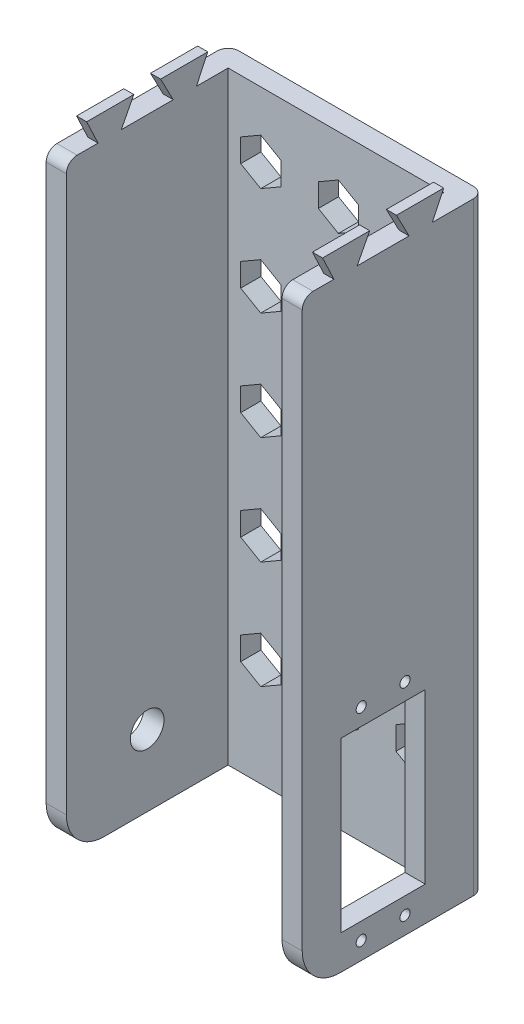
SolidWorks part; units mm, degrees
ref_plane "Front Plane" through (0, 0, 0) normal (0, 0, 1) x (1, 0, 0)
ref_plane "Top Plane" through (0, 0, 0) normal (0, 1, 0) x (1, 0, 0)
ref_plane "Right Plane" through (0, 0, 0) normal (1, 0, 0) x (0, 0, -1)
sketch "Sketch1" plane through (0, 0, 0) normal (0, 1, 0) x (1, 0, 0)
  line L0 (-38.9416, 17.4938) -> (21.3834, 17.4938)
  line L1 (21.3834, 17.4938) -> (21.3834, -25.3687)
  line L2 (21.3834, -25.3687) -> (16.6209, -25.3687)
  line L3 (16.6209, -25.3687) -> (16.6209, 12.7313)
  line L4 (16.6209, 12.7313) -> (-34.1791, 12.7313)
  line L5 (-34.1791, 12.7313) -> (-34.1791, -25.3687)
  line L6 (-34.1791, -25.3687) -> (-38.9416, -25.3687)
  line L7 (-38.9416, -25.3687) -> (-38.9416, 17.4938)
extrude "Boss-Extrude1" add sketch "Sketch1" along normal blind 152.4
sketch "Sketch2" plane through (21.3834, 0, 0) normal (1, 0, 0) x (0, 0, -1)
  line L0 (-25.3687, 38.1) -> (-6.3187, 38.1) construction
  line L1 (-25.3687, 152.4) -> (-25.3687, 0) construction
  line L2 (-6.3187, 38.1) -> (-6.3187, 0) construction
  line L3 (-25.3687, 0) -> (17.4938, 0) construction
  line L4 (-6.3187, 18.2562) -> (-11.4781, 18.2562) construction
  line L5 (-16.2406, 18.2562) -> (3.6031, 18.2562)
  line L6 (-16.2406, 18.2562) -> (-16.2406, 57.9437)
  line L7 (-16.2406, 57.9437) -> (3.6031, 57.9437)
  line L8 (3.6031, 18.2562) -> (3.6031, 57.9437)
  line L9 (-16.2406, 18.2562) -> (3.6031, 57.9437) construction
  line L10 (-16.2406, 57.9437) -> (3.6031, 18.2562) construction
  line L11 (-11.4781, 18.2562) -> (-11.4781, 14.2875) construction
  circle A0 centre (-11.4781, 14.2875) radius 1.1906
  circle A1 centre (-1.1594, 14.2875) radius 1.1906
  circle A2 centre (-1.1594, 61.9125) radius 1.1906
  circle A3 centre (-11.4781, 61.9125) radius 1.1906
  dimension "D1" = 19.05
  dimension "D2" = 38.1
  dimension "D3" = 19.8438
  dimension "D4" = 39.6875
extrude "Cut-Extrude1" cut sketch "Sketch2" against normal blind 6.35
sketch "Sketch3" plane through (21.3834, 0, 0) normal (1, 0, 0) x (0, 0, -1)
  line L0 (-20.5873, 5.6903) -> (-9.4704, 5.6903)
  line L1 (-9.4704, 5.6903) -> (-12.4312, 0)
  line L2 (-25.3687, 0) -> (17.4938, 0) construction
  line L3 (-12.4312, 0) -> (-17.9058, 0)
  line L4 (-17.9058, 0) -> (-20.5873, 5.6903)
  line L5 (-25.3687, 5.6903) -> (-15.0288, 5.6903) construction
  line L6 (-25.3687, 152.4) -> (-25.3687, 0) construction
  line L7 (-15.0288, 5.6903) -> (-15.1685, 0) construction
  line L8 (-15.1685, 0) -> (-25.3687, 0) construction
  line L9 (-25.3687, 0) -> (-6.3187, 0) construction
  line L10 (-6.3187, 0) -> (-6.3187, 14.3302) construction
  line L11 (-0.2063, 0) -> (5.2683, 0)
  line L12 (5.2683, 0) -> (7.9498, 5.6903)
  line L13 (-3.1671, 5.6903) -> (-0.2063, 0)
  line L14 (7.9498, 5.6903) -> (-3.1671, 5.6903)
  line L19 (-25.3687, 0) -> (12.7313, 0)
  line L20 (12.7313, 0) -> (12.7313, 152.4)
  line L21 (12.7313, 152.4) -> (-25.3687, 152.4)
  line L22 (-25.3687, 152.4) -> (-25.3687, 0)
  line L23 (-25.3687, 0) -> (12.7313, 0) construction
  dimension "D1" = 0
extrude "Cut-Extrude2" cut sketch "Sketch3" against normal blind 2.3813
sketch "Sketch4" plane through (-34.1791, 0, 0) normal (1, 0, 0) x (0, 0, -1)
  line L4 (-9.4704, 5.6903) -> (-20.5873, 5.6903)
  line L5 (-12.4312, 0) -> (-9.4704, 5.6903)
  line L6 (-17.9058, 0) -> (-12.4312, 0)
  line L7 (-20.5873, 5.6903) -> (-17.9058, 0)
  line L8 (-9.4704, 5.6903) -> (-20.5873, 5.6903)
  line L9 (-12.4312, 0) -> (-9.4704, 5.6903)
  line L10 (-17.9058, 0) -> (-12.4312, 0)
  line L11 (-20.5873, 5.6903) -> (-17.9058, 0)
  line L12 (5.2683, 0) -> (7.9498, 5.6903)
  line L13 (7.9498, 5.6903) -> (-3.1671, 5.6903)
  line L14 (-3.1671, 5.6903) -> (-0.2063, 0)
  line L15 (-0.2063, 0) -> (5.2683, 0)
  line L16 (5.2683, 0) -> (7.9498, 5.6903)
  line L17 (7.9498, 5.6903) -> (-3.1671, 5.6903)
  line L18 (-3.1671, 5.6903) -> (-0.2063, 0)
  line L19 (-0.2063, 0) -> (5.2683, 0)
  dimension "D1" = 0
  dimension "D2" = 0
extrude "Cut-Extrude3" cut sketch "Sketch4" against normal blind 2.3813
sketch "Sketch5" plane through (21.3834, 0, 0) normal (1, 0, 0) x (0, 0, -1)
  line L0 (-25.3687, 76.2) -> (28.2965, 76.2) construction
  line L1 (-25.3687, 152.4) -> (-25.3687, 0) construction
  line L2 (-3.1671, 146.7097) -> (-0.2063, 152.4) construction
  line L3 (-0.2063, 152.4) -> (5.2683, 152.4)
  line L4 (-9.4704, 5.6903) -> (-20.5873, 5.6903)
  line L5 (-12.4312, 0) -> (-9.4704, 5.6903)
  line L6 (-17.9058, 0) -> (-12.4312, 0)
  line L7 (-20.5873, 5.6903) -> (-17.9058, 0)
  line L8 (-9.4704, 5.6903) -> (-20.5873, 5.6903) construction
  line L9 (-12.4312, 0) -> (-9.4704, 5.6903) construction
  line L10 (-17.9058, 0) -> (-12.4312, 0) construction
  line L11 (-20.5873, 5.6903) -> (-17.9058, 0) construction
  line L12 (5.2683, 0) -> (7.9498, 5.6903)
  line L13 (7.9498, 5.6903) -> (-3.1671, 5.6903)
  line L14 (-3.1671, 5.6903) -> (-0.2063, 0)
  line L15 (-0.2063, 0) -> (5.2683, 0)
  line L16 (5.2683, 0) -> (7.9498, 5.6903) construction
  line L17 (7.9498, 5.6903) -> (-3.1671, 5.6903) construction
  line L18 (-3.1671, 5.6903) -> (-0.2063, 0) construction
  line L19 (-0.2063, 0) -> (5.2683, 0) construction
  line L20 (5.2683, 152.4) -> (7.9498, 146.7097) construction
  line L21 (7.9498, 146.7097) -> (-3.1671, 146.7097) construction
  line L22 (-20.5873, 146.7097) -> (-17.9058, 152.4) construction
  line L23 (-17.9058, 152.4) -> (-12.4312, 152.4)
  line L24 (-12.4312, 152.4) -> (-9.4704, 146.7097) construction
  line L25 (-9.4704, 146.7097) -> (-20.5873, 146.7097) construction
  line L26 (-25.3687, 152.4) -> (17.4938, 152.4) construction
  line L27 (7.9498, 158.0903) -> (-3.1671, 158.0903)
  line L28 (5.2683, 152.4) -> (7.9498, 158.0903)
  line L29 (-3.1671, 158.0903) -> (-0.2063, 152.4)
  line L30 (-12.4312, 152.4) -> (-9.4704, 158.0903)
  line L31 (-9.4704, 158.0903) -> (-20.5873, 158.0903)
  line L32 (-20.5873, 158.0903) -> (-17.9058, 152.4)
  dimension "D1" = 0
  dimension "D2" = 0
extrude "Boss-Extrude2" add sketch "Sketch5" against normal blind 2.3813
sketch "Sketch6" plane through (-34.1791, 0, 0) normal (1, 0, 0) x (0, 0, -1)
  line L4 (7.9498, 158.0903) -> (-3.1671, 158.0903)
  line L5 (-3.1671, 158.0903) -> (-0.2063, 152.4)
  line L6 (-0.2063, 152.4) -> (5.2683, 152.4)
  line L7 (5.2683, 152.4) -> (7.9498, 158.0903)
  line L8 (7.9498, 158.0903) -> (-3.1671, 158.0903)
  line L9 (-3.1671, 158.0903) -> (-0.2063, 152.4)
  line L10 (-0.2063, 152.4) -> (5.2683, 152.4)
  line L11 (5.2683, 152.4) -> (7.9498, 158.0903)
  line L12 (-25.3687, 0) -> (-17.9058, 0)
  line L13 (-17.9058, 0) -> (-20.5873, 5.6903)
  line L14 (-20.5873, 5.6903) -> (-9.4704, 5.6903)
  line L15 (-9.4704, 5.6903) -> (-12.4312, 0)
  line L16 (-12.4312, 0) -> (-0.2063, 0)
  line L17 (-0.2063, 0) -> (-3.1671, 5.6903)
  line L18 (-3.1671, 5.6903) -> (7.9498, 5.6903)
  line L19 (7.9498, 5.6903) -> (5.2683, 0)
  line L20 (5.2683, 0) -> (12.7313, 0)
  line L21 (12.7313, 0) -> (12.7313, 152.4)
  line L22 (12.7313, 152.4) -> (-25.3687, 152.4)
  line L23 (-25.3687, 152.4) -> (-25.3687, 0)
  line L24 (-25.3687, 0) -> (-17.9058, 0)
  line L25 (-17.9058, 0) -> (-20.5873, 5.6903)
  line L26 (-20.5873, 5.6903) -> (-9.4704, 5.6903)
  line L27 (-9.4704, 5.6903) -> (-12.4312, 0)
  line L28 (-12.4312, 0) -> (-0.2063, 0)
  line L29 (-0.2063, 0) -> (-3.1671, 5.6903)
  line L30 (-3.1671, 5.6903) -> (7.9498, 5.6903)
  line L31 (7.9498, 5.6903) -> (5.2683, 0)
  line L32 (5.2683, 0) -> (12.7313, 0)
  line L33 (12.7313, 0) -> (12.7313, 152.4)
  line L34 (12.7313, 152.4) -> (-25.3687, 152.4)
  line L35 (-25.3687, 152.4) -> (-25.3687, 0)
  line L36 (-17.9058, 152.4) -> (-12.4312, 152.4)
  line L37 (-12.4312, 152.4) -> (-9.4704, 158.0903)
  line L38 (-9.4704, 158.0903) -> (-20.5873, 158.0903)
  line L39 (-20.5873, 158.0903) -> (-17.9058, 152.4)
  line L40 (-17.9058, 152.4) -> (-12.4312, 152.4)
  line L41 (-12.4312, 152.4) -> (-9.4704, 158.0903)
  line L42 (-9.4704, 158.0903) -> (-20.5873, 158.0903)
  line L43 (-20.5873, 158.0903) -> (-17.9058, 152.4)
  line M31 (12.7313, 152.4) -> (-25.3687, 152.4)
  dimension "D1" = 0
  dimension "D2" = 0
  dimension "D3" = 0
extrude "Boss-Extrude3" add sketch "Sketch6" against normal blind 2.3813 contours L42 L43 L34 L41 | L11 L8 L9 M31
fillet "Fillet1" radius 2.54 6 edges at (19.0022, 0, 25.3687) (-36.5603, 0, 25.3687) (-36.5603, 152.4, 25.3687) (19.0022, 152.4, 25.3687) (-38.9416, 76.2, -17.4938) (21.3834, 76.2, -17.4938)
sketch "Sketch7" plane through (21.3834, 0, 0) normal (1, 0, 0) x (0, 0, -1)
  line L1 (-30.5416, 10.1931) -> (21.1328, 10.1931)
  line L2 (-30.5416, 10.1931) -> (-30.5416, -4.4953)
  line L3 (-30.5416, -4.4953) -> (21.1328, -4.4953)
  line L4 (21.1328, 10.1931) -> (21.1328, -4.4953)
extrude "Cut-Extrude4" cut sketch "Sketch7" against normal through all
fillet "Fillet2" radius 8.89 2 edges at (-36.5603, 10.1931, 25.3687) (19.0022, 10.1931, 25.3687)
sketch "Sketch8" plane through (-34.1791, 0, 0) normal (1, 0, 0) x (0, 0, -1)
  line L0 (-6.3187, 18.2562) -> (-6.3187, 26.9875) construction
  line L4 (-16.2406, 18.2562) -> (3.6031, 18.2562)
  line L5 (3.6031, 18.2562) -> (3.6031, 57.9437)
  line L6 (3.6031, 57.9437) -> (-16.2406, 57.9437)
  line L7 (-16.2406, 57.9437) -> (-16.2406, 18.2562)
  line L8 (-16.2406, 18.2562) -> (3.6031, 18.2562) construction
  line L9 (3.6031, 18.2562) -> (3.6031, 57.9437) construction
  line L10 (3.6031, 57.9437) -> (-16.2406, 57.9437) construction
  line L11 (-16.2406, 57.9437) -> (-16.2406, 18.2562) construction
  circle A0 centre (-6.3187, 26.9875) radius 3.9688
  circle A1 centre (-11.4781, 14.2875) radius 1.1906
  circle A2 centre (-11.4781, 14.2875) radius 1.1906 construction
  circle A3 centre (-11.4781, 61.9125) radius 1.1906
  circle A4 centre (-11.4781, 61.9125) radius 1.1906 construction
  circle A5 centre (-1.1594, 61.9125) radius 1.1906
  circle A6 centre (-1.1594, 61.9125) radius 1.1906 construction
  circle A7 centre (-1.1594, 14.2875) radius 1.1906
  circle A8 centre (-1.1594, 14.2875) radius 1.1906 construction
  dimension "D1" = 0
  dimension "D2" = 0
  dimension "D3" = 0
  dimension "D4" = 0
  dimension "D5" = 0
extrude "Cut-Extrude5" cut sketch "Sketch8" against normal through all
sketch "Sketch9" plane through (0, 0, -17.4938) normal (0, 0, -1) x (-1, 0, 0)
  line L0 (8.2018, 131.6427) -> (12.9262, 134.3704)
  line L1 (-10.0862, 131.6427) -> (-5.3618, 134.3704)
  line L2 (-5.3618, 134.3704) -> (-5.3618, 139.8257)
  line L3 (-5.3618, 139.8257) -> (-10.0862, 142.5534)
  line L4 (-10.0862, 142.5534) -> (-14.8107, 139.8257)
  line L5 (-14.8107, 139.8257) -> (-14.8107, 134.3704)
  line L6 (-14.8107, 134.3704) -> (-10.0862, 131.6427)
  line L7 (12.9262, 134.3704) -> (12.9262, 139.8257)
  line L8 (12.9262, 139.8257) -> (8.2018, 142.5534)
  line L9 (8.2018, 142.5534) -> (3.4773, 139.8257)
  line L10 (3.4773, 139.8257) -> (3.4773, 134.3704)
  line L11 (3.4773, 134.3704) -> (8.2018, 131.6427)
  line L12 (26.4898, 131.6427) -> (31.2142, 134.3704)
  line L13 (31.2142, 134.3704) -> (31.2142, 139.8257)
  line L14 (31.2142, 139.8257) -> (26.4898, 142.5534)
  line L15 (26.4898, 142.5534) -> (21.7653, 139.8257)
  line L16 (21.7653, 139.8257) -> (21.7653, 134.3704)
  line L17 (21.7653, 134.3704) -> (26.4898, 131.6427)
  line L18 (8.2018, 106.2427) -> (12.9262, 108.9704)
  line L19 (12.9262, 108.9704) -> (12.9262, 114.4257)
  line L20 (12.9262, 114.4257) -> (8.2018, 117.1534)
  line L21 (8.2018, 117.1534) -> (3.4773, 114.4257)
  line L22 (3.4773, 114.4257) -> (3.4773, 108.9704)
  line L23 (3.4773, 108.9704) -> (8.2018, 106.2427)
  line L24 (26.4898, 106.2427) -> (31.2142, 108.9704)
  line L25 (31.2142, 108.9704) -> (31.2142, 114.4257)
  line L26 (31.2142, 114.4257) -> (26.4898, 117.1534)
  line L27 (26.4898, 117.1534) -> (21.7653, 114.4257)
  line L28 (21.7653, 114.4257) -> (21.7653, 108.9704)
  line L29 (21.7653, 108.9704) -> (26.4898, 106.2427)
  line L30 (8.2018, 80.8427) -> (12.9262, 83.5704)
  line L31 (12.9262, 83.5704) -> (12.9262, 89.0257)
  line L32 (12.9262, 89.0257) -> (8.2018, 91.7534)
  line L33 (8.2018, 91.7534) -> (3.4773, 89.0257)
  line L34 (3.4773, 89.0257) -> (3.4773, 83.5704)
  line L35 (3.4773, 83.5704) -> (8.2018, 80.8427)
  line L36 (26.4898, 80.8427) -> (31.2142, 83.5704)
  line L37 (31.2142, 83.5704) -> (31.2142, 89.0257)
  line L38 (31.2142, 89.0257) -> (26.4898, 91.7534)
  line L39 (26.4898, 91.7534) -> (21.7653, 89.0257)
  line L40 (21.7653, 89.0257) -> (21.7653, 83.5704)
  line L41 (21.7653, 83.5704) -> (26.4898, 80.8427)
  line L42 (8.2018, 55.4427) -> (12.9262, 58.1704)
  line L43 (12.9262, 58.1704) -> (12.9262, 63.6257)
  line L44 (12.9262, 63.6257) -> (8.2018, 66.3534)
  line L45 (8.2018, 66.3534) -> (3.4773, 63.6257)
  line L46 (3.4773, 63.6257) -> (3.4773, 58.1704)
  line L47 (3.4773, 58.1704) -> (8.2018, 55.4427)
  line L48 (26.4898, 55.4427) -> (31.2142, 58.1704)
  line L49 (31.2142, 58.1704) -> (31.2142, 63.6257)
  line L50 (31.2142, 63.6257) -> (26.4898, 66.3534)
  line L51 (26.4898, 66.3534) -> (21.7653, 63.6257)
  line L52 (21.7653, 63.6257) -> (21.7653, 58.1704)
  line L53 (21.7653, 58.1704) -> (26.4898, 55.4427)
  line L54 (8.2018, 30.0427) -> (12.9262, 32.7704)
  line L55 (12.9262, 32.7704) -> (12.9262, 38.2257)
  line L56 (12.9262, 38.2257) -> (8.2018, 40.9534)
  line L57 (8.2018, 40.9534) -> (3.4773, 38.2257)
  line L58 (3.4773, 38.2257) -> (3.4773, 32.7704)
  line L59 (3.4773, 32.7704) -> (8.2018, 30.0427)
  line L60 (26.4898, 30.0427) -> (31.2142, 32.7704)
  line L61 (31.2142, 32.7704) -> (31.2142, 38.2257)
  line L62 (31.2142, 38.2257) -> (26.4898, 40.9534)
  line L63 (26.4898, 40.9534) -> (21.7653, 38.2257)
  line L64 (21.7653, 38.2257) -> (21.7653, 32.7704)
  line L65 (21.7653, 32.7704) -> (26.4898, 30.0427)
  line L66 (-10.0862, 106.2427) -> (-5.3618, 108.9704)
  line L67 (-5.3618, 108.9704) -> (-5.3618, 114.4257)
  line L68 (-5.3618, 114.4257) -> (-10.0862, 117.1534)
  line L69 (-10.0862, 117.1534) -> (-14.8107, 114.4257)
  line L70 (-14.8107, 114.4257) -> (-14.8107, 108.9704)
  line L71 (-14.8107, 108.9704) -> (-10.0862, 106.2427)
  line L72 (-10.0862, 80.8427) -> (-5.3618, 83.5704)
  line L73 (-5.3618, 83.5704) -> (-5.3618, 89.0257)
  line L74 (-5.3618, 89.0257) -> (-10.0862, 91.7534)
  line L75 (-10.0862, 91.7534) -> (-14.8107, 89.0257)
  line L76 (-14.8107, 89.0257) -> (-14.8107, 83.5704)
  line L77 (-14.8107, 83.5704) -> (-10.0862, 80.8427)
  line L78 (-10.0862, 55.4427) -> (-5.3618, 58.1704)
  line L79 (-5.3618, 58.1704) -> (-5.3618, 63.6257)
  line L80 (-5.3618, 63.6257) -> (-10.0862, 66.3534)
  line L81 (-10.0862, 66.3534) -> (-14.8107, 63.6257)
  line L82 (-14.8107, 63.6257) -> (-14.8107, 58.1704)
  line L83 (-14.8107, 58.1704) -> (-10.0862, 55.4427)
  line L84 (-10.0862, 30.0427) -> (-5.3618, 32.7704)
  line L85 (-5.3618, 32.7704) -> (-5.3618, 38.2257)
  line L86 (-5.3618, 38.2257) -> (-10.0862, 40.9534)
  line L87 (-10.0862, 40.9534) -> (-14.8107, 38.2257)
  line L88 (-14.8107, 38.2257) -> (-14.8107, 32.7704)
  line L89 (-14.8107, 32.7704) -> (-10.0862, 30.0427)
  circle A0 centre (-10.0862, 137.0981) radius 4.7245 construction
  dimension "D1" = 3
  dimension "D2" = 5
extrude "Cut-Extrude6" cut sketch "Sketch9" against normal through all
